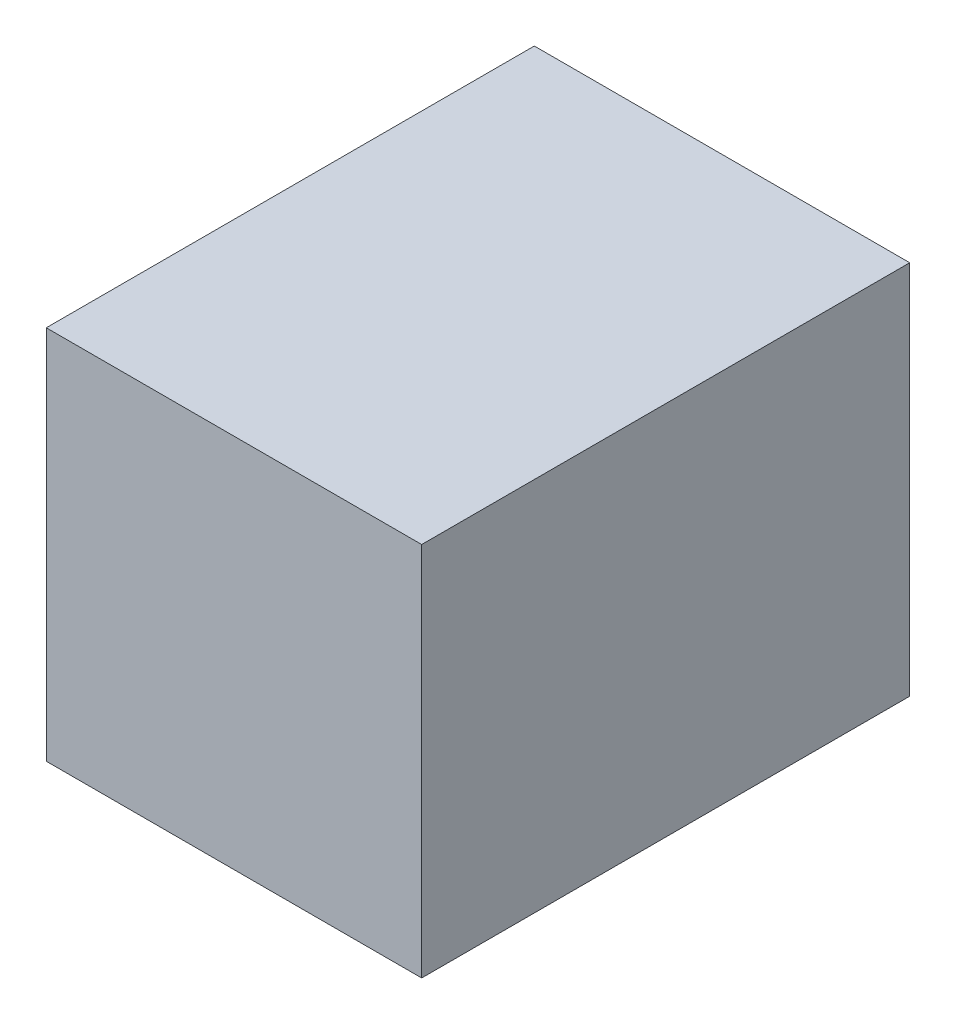
SolidWorks part; units mm, degrees
ref_plane "前视基准面" through (0, 0, 0) normal (0, 0, 1) x (1, 0, 0)
ref_plane "上视基准面" through (0, 0, 0) normal (0, 1, 0) x (1, 0, 0)
ref_plane "右视基准面" through (0, 0, 0) normal (1, 0, 0) x (0, 0, -1)
other "Configuration Table"
sketch "草图1" plane through (0, 0, 0) normal (0, 0, 1) x (1, 0, 0)
  line L1 (0, 0) -> (10, 0)
  line L2 (0, 0) -> (0, 10)
  line L3 (0, 10) -> (10, 10)
  line L4 (10, 0) -> (10, 10)
extrude "凸台-拉伸1" add sketch "草图1" along normal blind 10 and the other way blind 3
